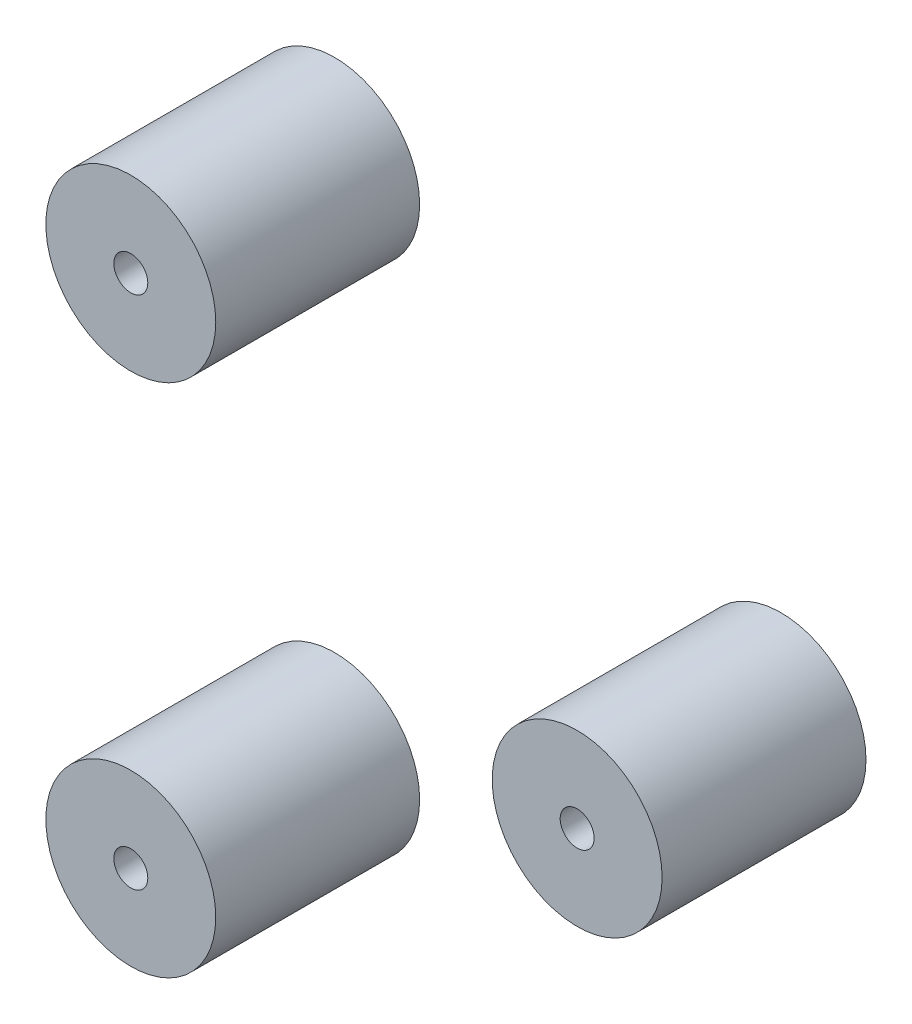
SolidWorks part; units mm, degrees
material "Plastique personnalisé"
ref_plane "Plan de face" through (0, 0, 0) normal (0, 0, 1) x (1, 0, 0)
ref_plane "Plan de dessus" through (0, 0, 0) normal (0, 1, 0) x (1, 0, 0)
ref_plane "Plan de droite" through (0, 0, 0) normal (1, 0, 0) x (0, 0, -1)
sketch "Esquisse1" plane through (0, 0, 0) normal (0, 0, 1) x (1, 0, 0)
  line L0 (0, 0) -> (60, 0) construction
  circle A0 centre (43.785, 0) radius 12.5
  circle A1 centre (-21.8925, -37.919) radius 12.5
  circle A2 centre (-21.8925, 37.919) radius 12.5
  circle A3 centre (-21.8925, 37.919) radius 2.5
  circle A4 centre (43.785, 0) radius 2.5
  circle A5 centre (-21.8925, -37.919) radius 2.5
  point P12 (0, 0)
  dimension "D2" = 3
  dimension "D1" = 60
extrude "Boss.-Extru.1" add sketch "Esquisse1" along normal blind 30
sketch "Esquisse2" plane through (0, 0, 30) normal (0, 0, 1) x (1, 0, 0)
  circle A0 centre (-21.8925, 37.919) radius 8
  circle A1 centre (43.785, 0) radius 8
  circle A2 centre (-21.8925, -37.919) radius 8
sketch "Esquisse3" plane through (0, 0, 0) normal (0, 0, -1) x (-1, 0, 0)
  circle A0 centre (21.8925, -37.919) radius 8
  circle A1 centre (-43.785, 0) radius 8
  circle A2 centre (21.8925, 37.919) radius 8
extrude "Enlèv. mat.-Extru.1" cut sketch "Esquisse3" against normal blind 25
